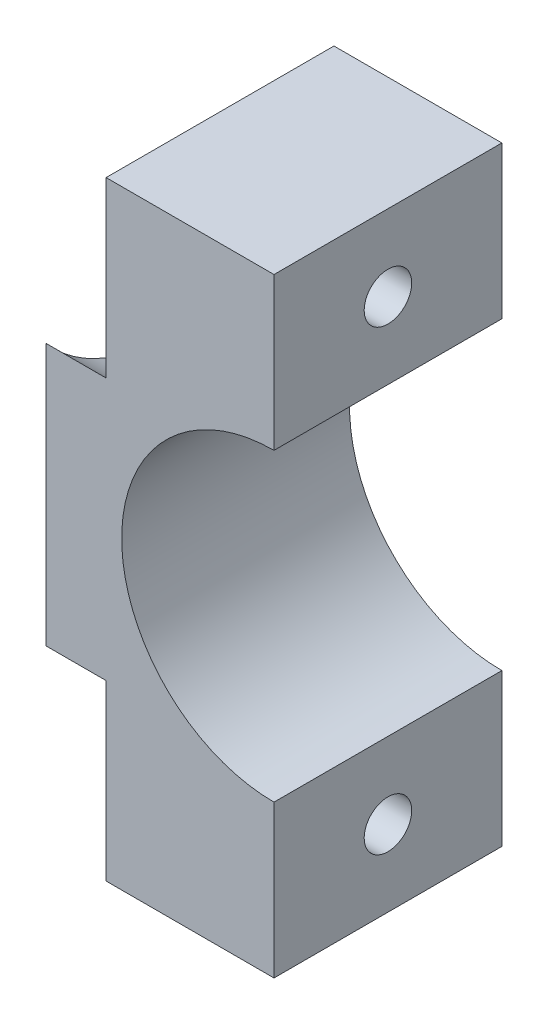
SolidWorks part; units mm, degrees
ref_plane "Front Plane" through (0, 0, 0) normal (1, 0, 0) x (0, 1, 0)
ref_plane "Top Plane" through (0, 0, 0) normal (0, 0, 1) x (0, 1, 0)
ref_plane "Right Plane" through (0, 0, 0) normal (0, 1, 0) x (-1, 0, 0)
sketch "Sketch2" plane through (0, 0, 0) normal (0, 0, 1) x (0, 1, 0)
  line L0 (0, 0) -> (0, 19) construction
  line L1 (10.925, 19) -> (-10.925, 19)
  line L2 (-10.925, 19) -> (-10.925, 14)
  line L3 (-25.4, 0) -> (-25.4, 14)
  line L4 (-25.4, 14) -> (-10.925, 14)
  line L5 (-25.4, 0) -> (-12.7, 0)
  line L6 (25.4, 0) -> (12.7, 0)
  line L7 (25.4, 14) -> (10.925, 14)
  line L8 (25.4, 0) -> (25.4, 14)
  line L9 (10.925, 19) -> (10.925, 14)
  arc A0 (12.7, 0) -> (-12.7, 0) centre (0, 0) ccw
  dimension "D3" = 12.7
  dimension "D1" = 21.85
  dimension "D2" = 5
  dimension "D4" = 25.4
  dimension "D5" = 50.8
extrude "Boss-Extrude1" add sketch "Sketch2" along normal blind 19 contours A0 L5 L3 L4 L2 L1 L9 L7 L8 L6
sketch "Sketch4" plane through (-14, 0, 0) normal (-1, 0, 0) x (0, 0, 1)
  line L0 (19, 25.4) -> (0, 25.4) construction
  line L1 (0, 25.4) -> (0, 10.925) construction
  line L2 (0, 0) -> (19, 0) construction
  line L3 (19, 10.925) -> (19, -10.925) construction
  circle A0 centre (9.5, 19.05) radius 1.9806
  circle A1 centre (9.5, -19.05) radius 1.9806
  dimension "D1" = 6.35
  dimension "D2" = 9.5
extrude "Cut-Extrude1" cut sketch "Sketch4" against normal through all contours A0 | A1
sketch "Sketch6" plane through (-19, 0, 0) normal (-1, 0, 0) x (0, -1, 0)
  circle A0 centre (-19.05, 9.5) radius 12.5
  circle A1 centre (19.05, 9.5) radius 12.5
  dimension "D1" = 25
  dimension "D2" = 25
extrude "Cut-Extrude2" cut sketch "Sketch6" against normal up to surface (5 mm away) up to face at (-14, 19.05, 11.4806)
